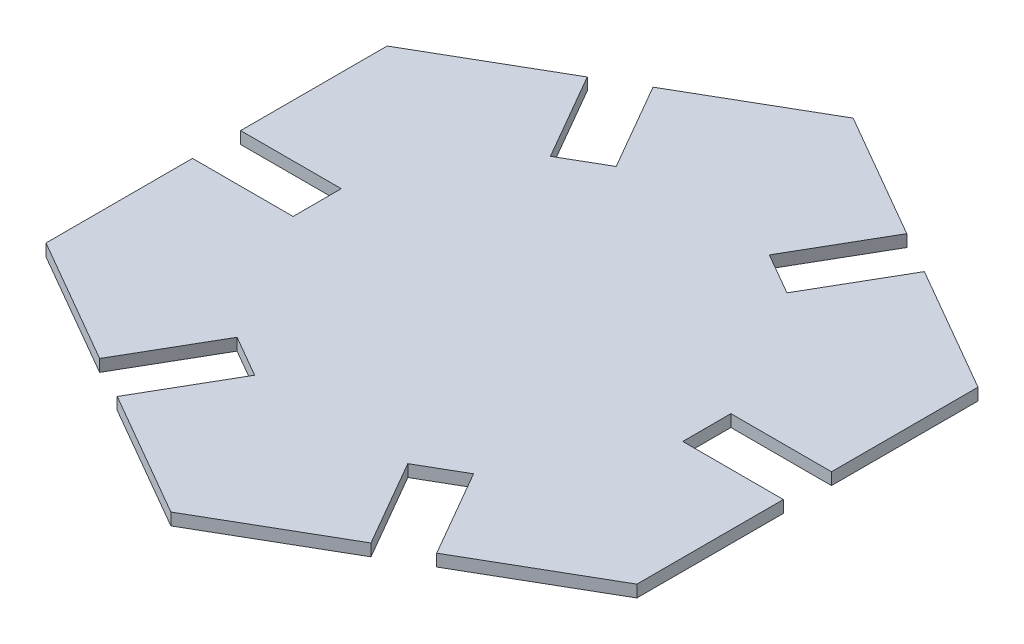
SolidWorks part; units mm, degrees
material "6061 Alloy"
ref_plane "Front Plane" through (0, 0, 0) normal (0, 0, 1) x (1, 0, 0)
ref_plane "Top Plane" through (0, 0, 0) normal (0, 1, 0) x (1, 0, 0)
ref_plane "Right Plane" through (0, 0, 0) normal (1, 0, 0) x (0, 0, -1)
sketch "Sketch1" plane through (0, 0, 0) normal (0, 1, 0) x (1, 0, 0)
  line L0 (26.2212, 24.6438) -> (-12.7499, 47.1438)
  line L1 (-12.7499, 47.1438) -> (-51.7211, 24.6438)
  line L2 (-51.7211, 24.6438) -> (-51.7211, -20.3562)
  line L3 (-51.7211, -20.3562) -> (-12.7499, -42.8562)
  line L4 (-12.7499, -42.8562) -> (26.2212, -20.3562)
  line L5 (26.2212, -20.3562) -> (26.2212, 24.6438)
  line L6 (9.4853, 34.3063) -> (3.986, 37.4813)
  line L7 (-29.4859, 37.4813) -> (-34.9851, 34.3063)
  line L8 (-51.7211, 24.6438) -> (-51.7211, -1.0312)
  line L9 (-34.9851, -30.0187) -> (-29.4859, -33.1937)
  line L10 (3.986, -33.1937) -> (9.4853, -30.0187)
  line L11 (26.2212, -1.0312) -> (26.2212, 5.3188)
  line L12 (-51.7211, -1.0312) -> (-38.4499, -1.0312)
  line L14 (-38.4499, 5.3188) -> (-51.7211, 5.3188)
  line L16 (-34.9851, 34.3063) -> (-28.3496, 22.8131)
  line L18 (-22.8503, 25.9881) -> (-29.4859, 37.4813)
  line L20 (3.986, 37.4813) -> (-2.6496, 25.9881)
  line L22 (2.8497, 22.8131) -> (9.4853, 34.3063)
  line L24 (26.2212, 5.3188) -> (12.9501, 5.3188)
  line L26 (12.9501, -1.0312) -> (26.2212, -1.0312)
  line L28 (9.4853, -30.0187) -> (2.8497, -18.5256)
  line L30 (-2.6496, -21.7006) -> (3.986, -33.1937)
  line L32 (-29.4859, -33.1937) -> (-22.8503, -21.7006)
  line L33 (-28.3496, -18.5256) -> (-34.9851, -30.0187)
  line L35 (-28.3496, -18.5256) -> (-22.8503, -21.7006)
  line L36 (-51.7211, 5.3188) -> (-51.7211, -1.0312)
  line L37 (-38.4499, 5.3188) -> (-38.4499, -1.0312)
  line L38 (-28.3496, 22.8131) -> (-22.8503, 25.9881)
  line L40 (-2.6496, 25.9881) -> (2.8497, 22.8131)
  line L42 (12.9501, 5.3188) -> (12.9501, -1.0312)
  line L44 (2.8497, -18.5256) -> (-2.6496, -21.7006)
  circle A0 centre (-12.7499, 2.1438) radius 38.9711 construction
extrude "Boss-Extrude1" add sketch "Sketch1" along normal blind 1.5875 contours L1 L2 L3 L4 L5 L0
sketch "Sketch2" plane through (0, 1.5875, 0) normal (0, 1, 0) x (1, 0, 0)
  line L0 (9.4853, 34.3063) -> (3.986, 37.4813)
  line L1 (-29.4859, 37.4813) -> (-34.9851, 34.3063)
  line L2 (-51.7211, 5.3188) -> (-51.7211, -1.0312)
  line L3 (-34.9851, -30.0187) -> (-29.4859, -33.1937)
  line L4 (3.986, -33.1937) -> (9.4853, -30.0187)
  line L5 (26.2212, -1.0312) -> (26.2212, 5.3188)
  line L6 (9.4853, 34.3063) -> (3.986, 37.4813)
  line L7 (-29.4859, 37.4813) -> (-34.9851, 34.3063)
  line L8 (-51.7211, 5.3188) -> (-51.7211, -1.0312)
  line L9 (-34.9851, -30.0187) -> (-29.4859, -33.1937)
  line L10 (3.986, -33.1937) -> (9.4853, -30.0187)
  line L11 (26.2212, -1.0312) -> (26.2212, 5.3188)
  line L12 (-51.7211, -1.0312) -> (-38.4499, -1.0312)
  line L13 (-38.4499, 5.3188) -> (-51.7211, 5.3188)
  line L14 (-34.9851, 34.3063) -> (-28.3496, 22.8131)
  line L15 (-22.8503, 25.9881) -> (-29.4859, 37.4813)
  line L16 (3.986, 37.4813) -> (-2.6496, 25.9881)
  line L17 (2.8497, 22.8131) -> (9.4853, 34.3063)
  line L18 (26.2212, 5.3188) -> (12.9501, 5.3188)
  line L19 (12.9501, -1.0312) -> (26.2212, -1.0312)
  line L20 (9.4853, -30.0187) -> (2.8497, -18.5256)
  line L21 (-2.6496, -21.7006) -> (3.986, -33.1937)
  line L22 (-29.4859, -33.1937) -> (-22.8503, -21.7006)
  line L23 (-28.3496, -18.5256) -> (-34.9851, -30.0187)
  line L24 (-28.3496, -18.5256) -> (-22.8503, -21.7006)
  line L25 (-51.7211, 5.3188) -> (-51.7211, -1.0312)
  line L26 (-38.4499, 5.3188) -> (-38.4499, -1.0312)
  line L27 (-28.3496, 22.8131) -> (-22.8503, 25.9881)
  line L28 (-2.6496, 25.9881) -> (2.8497, 22.8131)
  line L29 (12.9501, 5.3188) -> (12.9501, -1.0312)
  line L30 (2.8497, -18.5256) -> (-2.6496, -21.7006)
  arc A0 (-51.5915, 5.3188) -> (-51.5915, -1.0312) centre (-12.7499, 2.1438) ccw construction
  arc A1 (-29.4211, 37.3691) -> (-34.9204, 34.1941) centre (-12.7499, 2.1438) ccw construction
  arc A2 (9.4205, 34.1941) -> (3.9212, 37.3691) centre (-12.7499, 2.1438) ccw construction
  arc A3 (26.0917, -1.0312) -> (26.0917, 5.3188) centre (-12.7499, 2.1438) ccw construction
  arc A4 (3.9212, -33.0815) -> (9.4205, -29.9065) centre (-12.7499, 2.1438) ccw construction
  arc A5 (-34.9204, -29.9065) -> (-29.4211, -33.0815) centre (-12.7499, 2.1438) ccw construction
  line M11 (26.2212, 24.6438) -> (-12.7499, 47.1438)
  line M12 (-12.7499, 47.1438) -> (-51.7211, 24.6438)
  line M13 (-51.7211, 24.6438) -> (-51.7211, -20.3562)
  line M14 (-51.7211, -20.3562) -> (-12.7499, -42.8562)
  line M15 (-12.7499, -42.8562) -> (26.2212, -20.3562)
  line M16 (26.2212, -20.3562) -> (26.2212, 24.6438)
extrude "Cut-Extrude1" cut sketch "Sketch2" against normal through all contours L18 L29 L19 M16 | L16 L28 L17 M11 | L14 L27 L15 M12 | L26 L13 L12 M13 | L20 L30 L21 M15 | L24 L23 L22 M14
